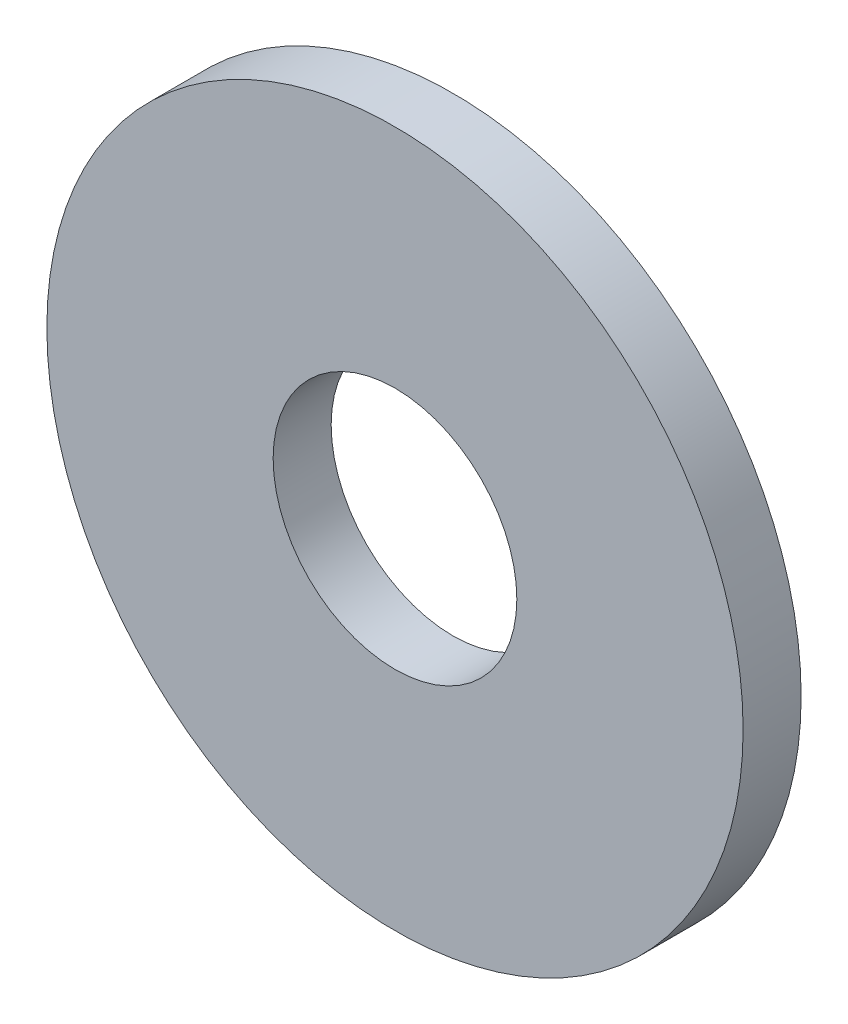
SolidWorks part; units mm, degrees
ref_plane "Спереди" through (0, 0, 0) normal (0, 0, 1) x (1, 0, 0)
ref_plane "Сверху" through (0, 0, 0) normal (0, 1, 0) x (1, 0, 0)
ref_plane "Справа" through (0, 0, 0) normal (1, 0, 0) x (0, 0, -1)
sketch "Эскиз1" plane through (0, 0, 0) normal (0, 0, 1) x (1, 0, 0)
  circle A0 centre (0, 0) radius 12
  circle A1 centre (0, 0) radius 4.2
  dimension "D1" = 8.4
  dimension "D2" = 24
extrude "Бобышка-Вытянуть1" add sketch "Эскиз1" along normal blind 2
